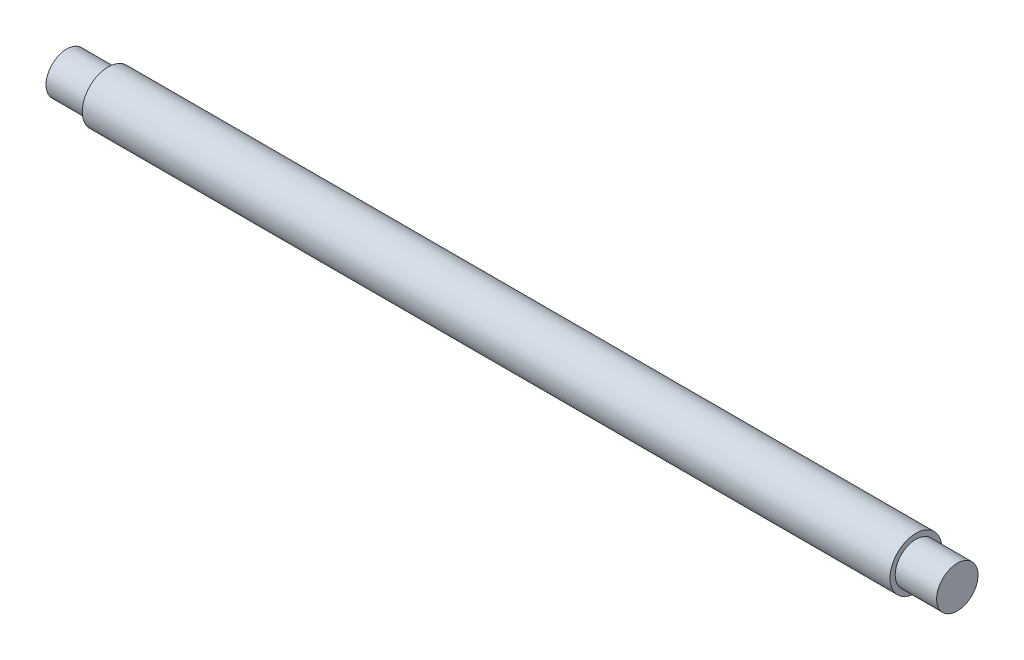
SolidWorks part; units mm, degrees
ref_plane "Front Plane" through (0, 0, 0) normal (0, 0, 1) x (1, 0, 0)
ref_plane "Top Plane" through (0, 0, 0) normal (0, 1, 0) x (1, 0, 0)
ref_plane "Right Plane" through (0, 0, 0) normal (1, 0, 0) x (0, 0, -1)
sketch "Sketch1" plane through (0, 0, 0) normal (0, 0, 1) x (1, 0, 0)
  line L0 (0, 0) -> (188.9456, 0) construction
  line L1 (0, 0) -> (0, 4)
  line L2 (0, 4) -> (8, 4)
  line L3 (8, 4) -> (8, 5)
  line L4 (8, 5) -> (164, 5)
  line L5 (164, 5) -> (164, 4)
  line L6 (164, 4) -> (172, 4)
  line L7 (172, 4) -> (172, 0)
  line L8 (0, 0) -> (172, 0)
  dimension "D1" = 8
  dimension "D2" = 8
  dimension "D3" = 10
  dimension "D4" = 172
revolve "Revolve1" add sketch "Sketch1" angle 360 about L0
